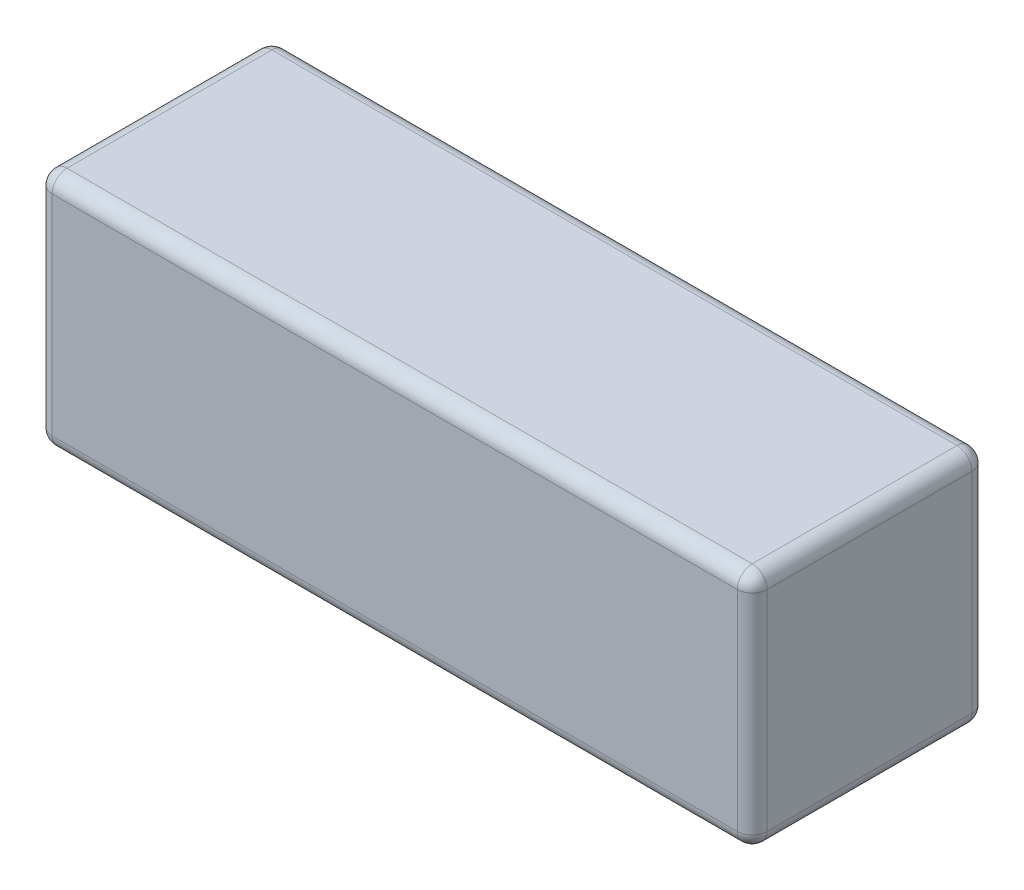
SolidWorks part; units mm, degrees
material "TurnigyBatt"
ref_plane "Front Plane" through (0, 0, 0) normal (0, 0, 1) x (1, 0, 0)
ref_plane "Top Plane" through (0, 0, 0) normal (0, 1, 0) x (1, 0, 0)
ref_plane "Right Plane" through (0, 0, 0) normal (1, 0, 0) x (0, 0, -1)
other "Center of Mass"
sketch "Sketch1" plane through (0, 0, 0) normal (0, 1, 0) x (1, 0, 0)
  line L1 (76.2, -25) -> (-76.2, -25)
  line L2 (76.2, -25) -> (76.2, 25)
  line L3 (76.2, 25) -> (-76.2, 25)
  line L4 (-76.2, -25) -> (-76.2, 25)
  line L5 (76.2, -25) -> (-76.2, 25) construction
  line L6 (76.2, 25) -> (-76.2, -25) construction
  point P0 (0, 0)
  dimension "D1" = 50
  dimension "D2" = 152.4
extrude "Boss-Extrude1" add sketch "Sketch1" along normal blind 51
fillet "Fillet1" radius 3.175 12 edges at (0, 0, -25) (76.2, 25.5, -25) (76.2, 0, 0) (76.2, 25.5, 25) (0, 0, 25) (-76.2, 25.5, -25) (-76.2, 25.5, 25) (-76.2, 0, 0) (0, 51, -25) (76.2, 51, 0) (0, 51, 25) (-76.2, 51, 0)
